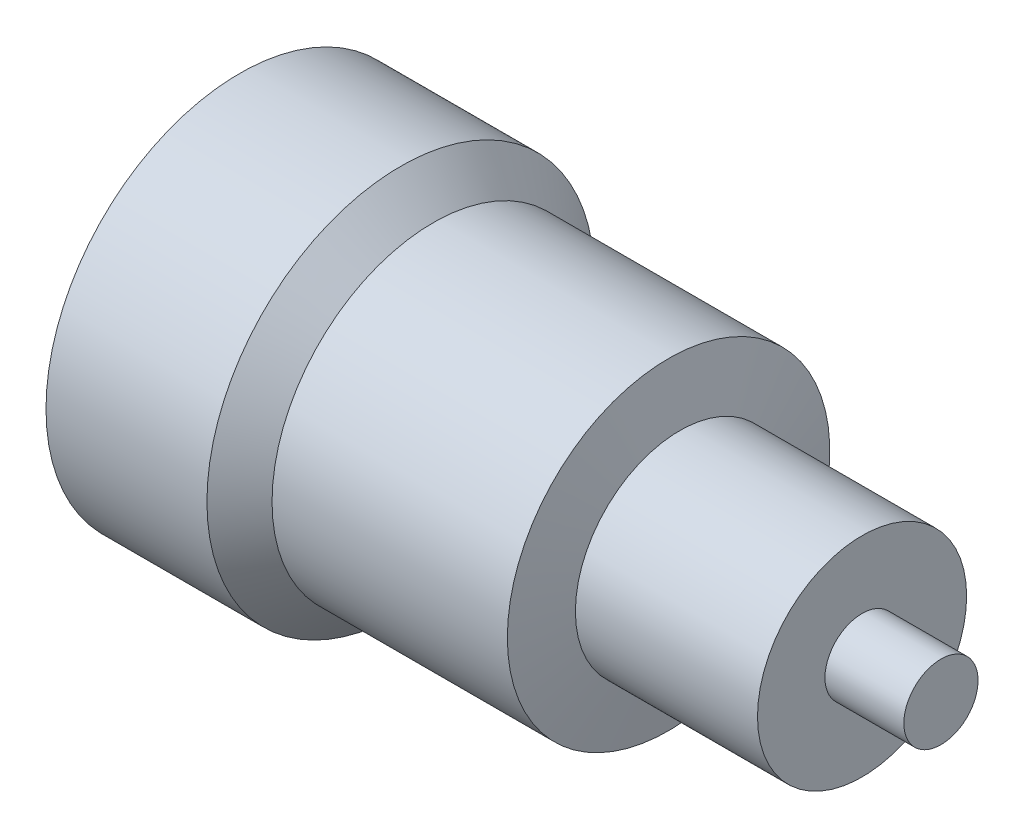
SolidWorks part; units mm, degrees
ref_plane "前基準面" through (0, 0, 0) normal (0, 0, 1) x (1, 0, 0)
ref_plane "上基準面" through (0, 0, 0) normal (0, 1, 0) x (1, 0, 0)
ref_plane "右基準面" through (0, 0, 0) normal (1, 0, 0) x (0, 0, -1)
sketch "草圖1" plane through (0, 0, 0) normal (0, 0, 1) x (1, 0, 0)
  line L0 (0, 0) -> (86.9726, 0) construction
  line L1 (0, 24.0385) -> (19.9615, 24.0385)
  line L2 (19.9615, 24.0385) -> (24, 20)
  line L3 (24, 20) -> (53.1873, 20)
  line L4 (53.1873, 20) -> (54.5984, 12.9711)
  line L5 (54.5984, 12.9711) -> (77.1873, 12.9711)
  line L6 (77.1873, 12.9711) -> (77.1873, 4.6044)
  line L7 (0, 24.0385) -> (0, 20)
  line L8 (0, 0) -> (86.9726, 0)
  line L9 (0, 20) -> (19.499, 20)
  line L10 (19.499, 20) -> (34.6606, 0)
  line L11 (34.6606, 0) -> (62.9893, 0)
  line L13 (86.9726, 4.6044) -> (77.1873, 4.6044)
  line L14 (86.9726, 4.6044) -> (86.9726, 0)
  point P5 (53.1873, 20)
  dimension "D1" = 20
  dimension "D2" = 24.0385
  dimension "D3" = 24
  dimension "D4" = 24
  dimension "D5" = 135
revolve "旋轉1" add sketch "草圖1" angle 360 about L8
